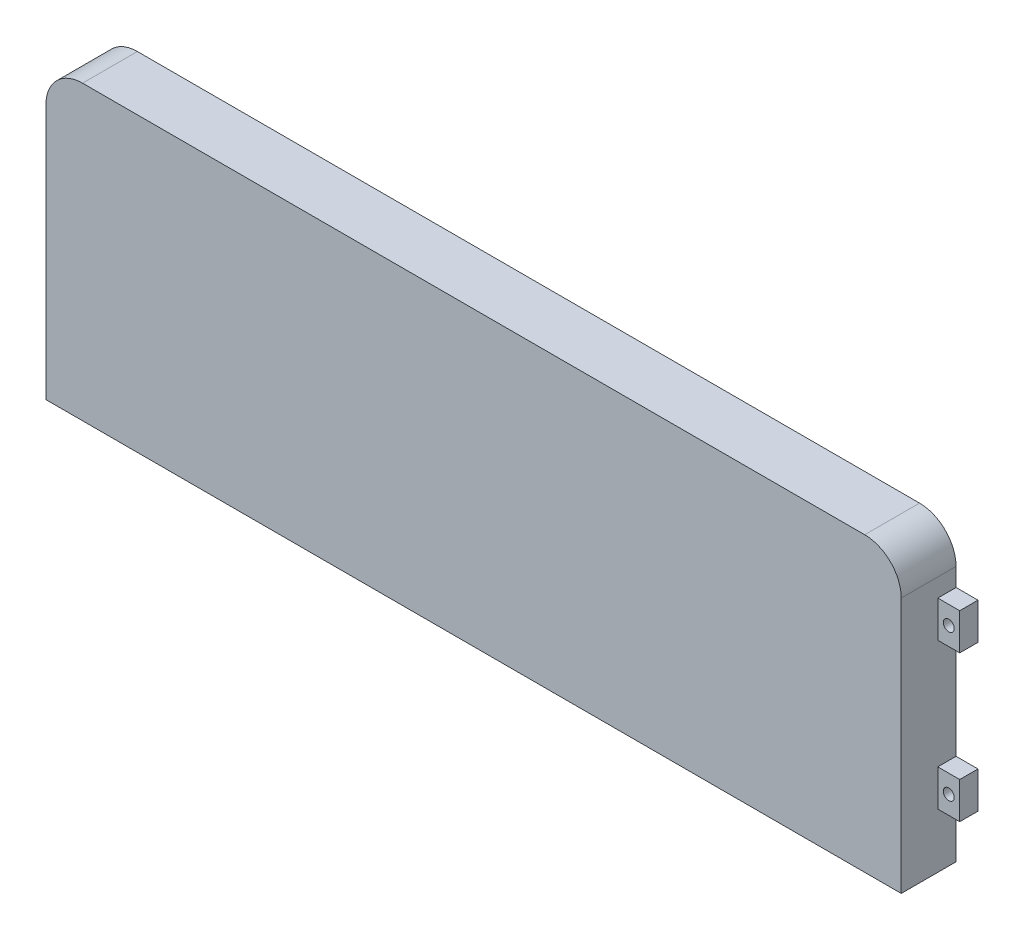
SolidWorks part; units mm, degrees
ref_plane "Plan de face" through (0, 0, 0) normal (0, 0, 1) x (1, 0, 0)
ref_plane "Plan de dessus" through (0, 0, 0) normal (0, 1, 0) x (1, 0, 0)
ref_plane "Plan de droite" through (0, 0, 0) normal (1, 0, 0) x (0, 0, -1)
sketch "Esquisse1" plane through (0, 0, 0) normal (0, 0, 1) x (1, 0, 0)
  line L1 (-107, 40) -> (107, 40)
  line L2 (-117, 30) -> (-117, -40)
  line L3 (-117, -40) -> (117, -40)
  line L4 (117, 30) -> (117, -40)
  line L5 (-117, 40) -> (117, -40) construction
  line L6 (-117, -40) -> (117, 40) construction
  arc A1 (107, 40) -> (117, 30) centre (107, 30) cw
  arc A3 (-107, 40) -> (-117, 30) centre (-107, 30) ccw
  point P0 (0, 0)
  dimension "D1" = 234
  dimension "D2" = 80
extrude "Boss.-Extru.1" add sketch "Esquisse1" along normal blind 15
shell "Coque1" thickness 3
sketch "Esquisse2" plane through (0, 0, 0) normal (0, 0, -1) x (-1, 0, 0)
  line L0 (0, 216.3025) -> (0, -77.6685)
  line L1 (-142.5224, 0) -> (151.2099, 0) construction
  line L2 (-117, -40) -> (-117, 30) construction
  line L3 (-123, 25) -> (-117, 25)
  line L4 (-123, 25) -> (-123, 15)
  line L5 (-123, 15) -> (-117, 15)
  line L6 (-117, 25) -> (-117, 15)
  line L7 (-123, 25) -> (-117, 15) construction
  line L8 (-123, 15) -> (-117, 25) construction
  line L9 (-123, -15) -> (-117, -15)
  line L10 (-117, -25) -> (-117, -15)
  line L11 (-123, -25) -> (-117, -25)
  line L12 (-123, -25) -> (-123, -15)
  line L13 (123, -25) -> (123, -15)
  line L14 (123, -25) -> (117, -25)
  line L15 (117, -25) -> (117, -15)
  line L16 (123, -15) -> (117, -15)
  line L17 (123, 15) -> (117, 15)
  line L18 (117, 25) -> (117, 15)
  line L19 (123, 25) -> (117, 25)
  line L20 (123, 25) -> (123, 15)
  circle A0 centre (-120, 20) radius 1.5
  circle A1 centre (-120, -20) radius 1.5
  circle A2 centre (120, -20) radius 1.5
  circle A3 centre (120, 20) radius 1.5
  point P4 (0, 69.317)
  point P6 (-120, 20)
  line M28 (117, -40) -> (117, 30)
  line M32 (-117, 30) -> (-117, -40)
  dimension "D4" = 3
  dimension "D1" = 6
  dimension "D2" = 10
  dimension "D3" = 20
sketch "Esquisse3" plane through (0, 0, 0) normal (0, 0, -1) x (-1, 0, 0)
  line L1 (117, -40) -> (-117, -40) construction
  line L2 (114, -40) -> (-114, -40)
  line L3 (-114, -37) -> (114, -37)
  line L8 (-114, -37) -> (-114, -40)
  line L9 (114, -37) -> (114, -40)
  line L20 (-117, 30) -> (-117, -40)
  line L21 (-117, -40) -> (117, -40)
  line L22 (117, -40) -> (117, 30)
  line L31 (107, 40) -> (-107, 40)
  arc A2 (117, 30) -> (107, 40) centre (107, 30) ccw
  arc A3 (-107, 40) -> (-117, 30) centre (-107, 30) ccw
  line M23 (114, -37) -> (-114, -37)
  line M30 (-117, -40) -> (117, -40)
  dimension "D1" = 0
extrude "Enlèv. mat.-Extru.2" cut sketch "Esquisse3" against normal up to surface (12 mm away) contours L9 L8 M23 M30 up to face at (0, 10.4832, 12)
sketch "Esquisse4" plane through (114, 0, 0) normal (-1, 0, 0) x (0, 0, 1)
  line L0 (0, -40) -> (0, 30) construction
  line L1 (0, -40) -> (0, 30)
  line L4 (5, -40) -> (5, 30)
  line L5 (12, 30) -> (0, 30) construction
  line L6 (0, 30) -> (5, 30)
  line L7 (0, -40) -> (1.25, -40)
  line L8 (12, -40) -> (0, -40) construction
  line L9 (5, -40) -> (3.75, -40)
  line L11 (1.25, -40) -> (1.25, 28.5)
  line L12 (2.5, -41.7548) -> (2.5, 64.6357) construction
  line L13 (3.75, -40) -> (3.75, 28.5)
  line L14 (1.25, 28.5) -> (3.75, 28.5)
  dimension "D1" = 2.5
  dimension "D2" = 1.25
  dimension "D3" = 1.25
  dimension "D4" = 1.5
extrude "Boss.-Extru.3" add sketch "Esquisse4" along normal blind 5
mirror "Symétrie1" about plane through (0, 0, 0) normal (1, 0, 0) of "Boss.-Extru.3"
sketch "Esquisse5" plane through (0, 0, 0) normal (0, 0, -1) x (-1, 0, 0)
  line L0 (-107, 37) -> (107, 37) construction
  line L1 (-107, 37) -> (107, 37)
  line L2 (-114, 30) -> (114, 30)
  arc A0 (114, 30) -> (107, 37) centre (107, 30) ccw construction
  arc A1 (-107, 37) -> (-114, 30) centre (-107, 30) ccw construction
  arc A2 (114, 30) -> (107, 37) centre (107, 30) ccw
  arc A3 (-107, 37) -> (-114, 30) centre (-107, 30) ccw
extrude "Boss.-Extru.4" add sketch "Esquisse5" against normal blind 5
extrude "Boss.-Extru.6" add sketch "Esquisse2" against normal blind 5 contours L12 L11 L9 A1 M32 | L4 L5 L3 A0 M32 | L20 L19 L17 A3 M28 | L13 L16 L14 A2 M28
sketch "Esquisse9" plane through (0, -40, 0) normal (0, -1, 0) x (1, 0, 0)
  line L0 (-114, 12) -> (-114, 5) construction
  line L1 (-114, 12) -> (-114, 5)
  line L2 (114, 12) -> (-114, 12) construction
  line L3 (114, 12) -> (-114, 12)
  line L4 (114, 12) -> (114, 5) construction
  line L5 (114, 12) -> (114, 5)
  line L6 (112, 10) -> (112, 5)
  line L7 (112, 10) -> (-112, 10)
  line L8 (-112, 10) -> (-112, 5)
  line L9 (-114, 5) -> (-112, 5)
  line L10 (112, 5) -> (114, 5)
  dimension "D1" = 2
